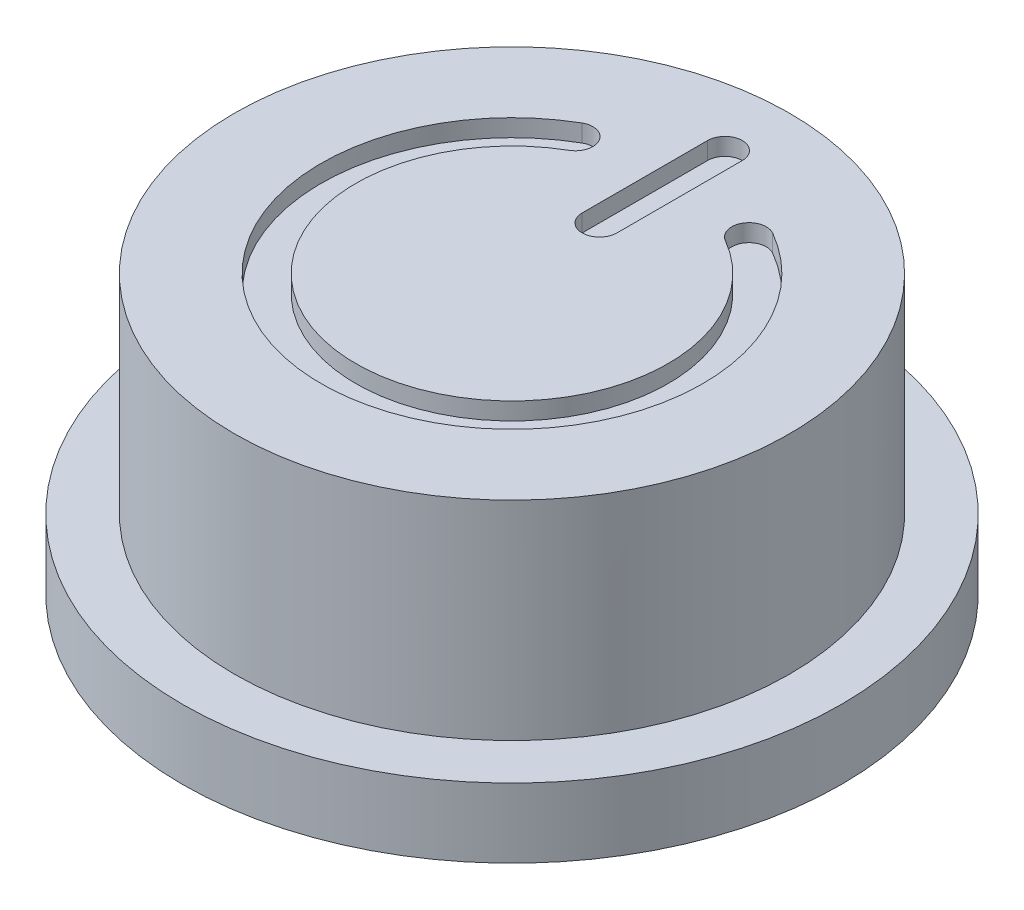
SolidWorks part; units mm, degrees
ref_plane "Front Plane" through (0, 0, 0) normal (0, 0, 1) x (1, 0, 0)
ref_plane "Top Plane" through (0, 0, 0) normal (0, 1, 0) x (1, 0, 0)
ref_plane "Right Plane" through (0, 0, 0) normal (1, 0, 0) x (0, 0, -1)
sketch "Sketch1" plane through (0, 0, 0) normal (0, 1, 0) x (1, 0, 0)
  circle A0 centre (0, 0) radius 8
  dimension "D1" = 16
extrude "Boss-Extrude1" add sketch "Sketch1" along normal blind 6
sketch "Sketch2" plane through (0, 0, 0) normal (0, -1, 0) x (1, 0, 0)
  circle A0 centre (0, 0) radius 9.5
  circle A1 centre (0, 0) radius 8 construction
  dimension "D1" = 1.5
extrude "Boss-Extrude2" add sketch "Sketch2" along normal blind 2
sketch "Sketch3" plane through (0, -2, 0) normal (0, -1, 0) x (1, 0, 0)
  circle A0 centre (0, 0) radius 6.25
  circle A1 centre (0, 0) radius 4.25
  dimension "D1" = 12.5
  dimension "D2" = 2
extrude "Cut-Extrude1" cut sketch "Sketch3" against normal blind 5
chamfer "Chamfer1" distance 1 angle 45 1 edges at (0, -2, -6.25)
chamfer "Chamfer2" distance 1 angle 45 1 edges at (0, -2, -4.25)
sketch "Sketch5" plane through (0, -2, 0) normal (0, -1, 0) x (1, 0, 0)
  line L0 (0, 12.8282) -> (0, -13.904) construction
  line L1 (-1.25, -16.5477) -> (1.25, -16.5477)
  line L2 (1.25, -16.5477) -> (1.25, -7.9017)
  line L4 (-1.25, -16.5477) -> (-1.25, -7.9017)
  arc A0 (1.25, -7.9017) -> (-1.25, -7.9017) centre (0, 0) cw
  dimension "D1" = 8
  dimension "D2" = 2.5
extrude "Cut-Extrude2" cut sketch "Sketch5" against normal through all
sketch "Sketch6" plane through (0, 6, 0) normal (0, 1, 0) x (1, 0, 0)
  line L0 (0, 10.5269) -> (0, -10.8778) construction
  line L1 (0, 6.1368) -> (0, 2.5234) construction
  line L2 (0.5, 6.1368) -> (0.5, 2.5234)
  line L3 (-0.5, 6.1368) -> (-0.5, 2.5234)
  line L4 (-9.2269, 4.3301) -> (10.5336, 4.3301) construction
  arc A0 (0.5, 6.1368) -> (-0.5, 6.1368) centre (0, 6.1368) ccw
  arc A1 (2.5, 4.3301) -> (-2.5, 4.3301) centre (0, 0) cw construction
  arc A2 (-2.75, 4.7631) -> (2.75, 4.7631) centre (0, 0) ccw
  arc A3 (-2.25, 3.8971) -> (2.25, 3.8971) centre (0, 0) ccw
  arc A4 (-2.25, 3.8971) -> (-2.75, 4.7631) centre (-2.5, 4.3301) ccw
  arc A5 (2.75, 4.7631) -> (2.25, 3.8971) centre (2.5, 4.3301) ccw
  arc A6 (-0.5, 2.5234) -> (0.5, 2.5234) centre (0, 2.5234) ccw
  point P8 (0, -5)
  point P13 (0, 4.3301)
  dimension "D1" = 0.5
  dimension "D2" = 5
  dimension "D3" = 5
extrude "Cut-Extrude3" cut sketch "Sketch6" against normal blind 0.5
